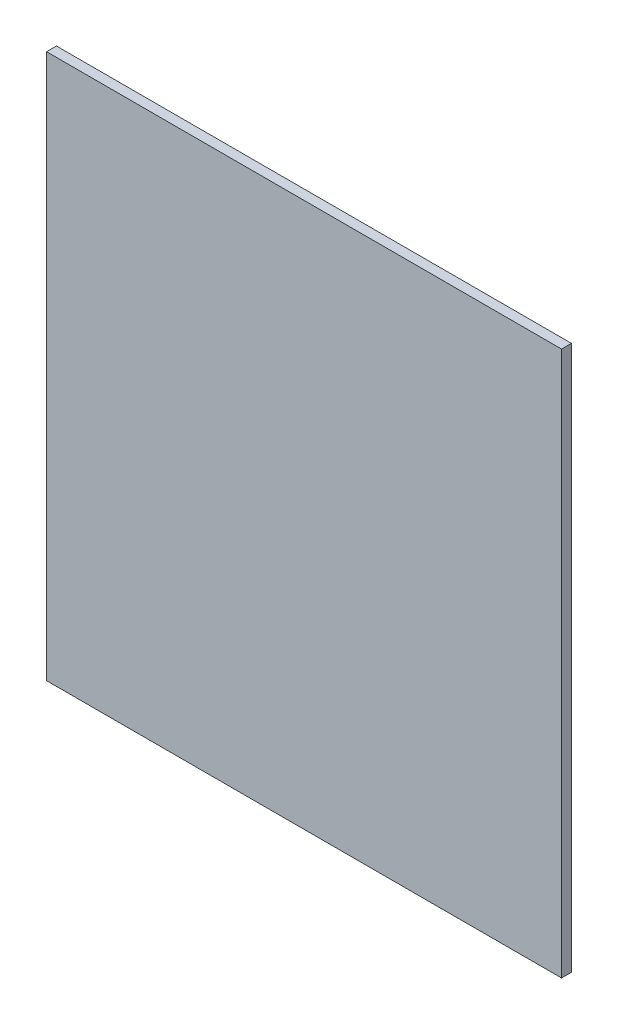
SolidWorks part; units mm, degrees
ref_plane "Plan de face" through (0, 0, 0) normal (0, 0, 1) x (1, 0, 0)
ref_plane "Plan de dessus" through (0, 0, 0) normal (0, 1, 0) x (1, 0, 0)
ref_plane "Plan de droite" through (0, 0, 0) normal (1, 0, 0) x (0, 0, -1)
sketch "Esquisse1" plane through (0, 0, 0) normal (0, 0, 1) x (1, 0, 0)
  line L1 (0, 0) -> (-312, 0)
  line L2 (0, 0) -> (0, 330)
  line L3 (0, 330) -> (-312, 330)
  line L4 (-312, 0) -> (-312, 330)
  dimension "D1" = 330
  dimension "D2" = 312
extrude "Boss.-Extru.1" add sketch "Esquisse1" along normal blind 6
